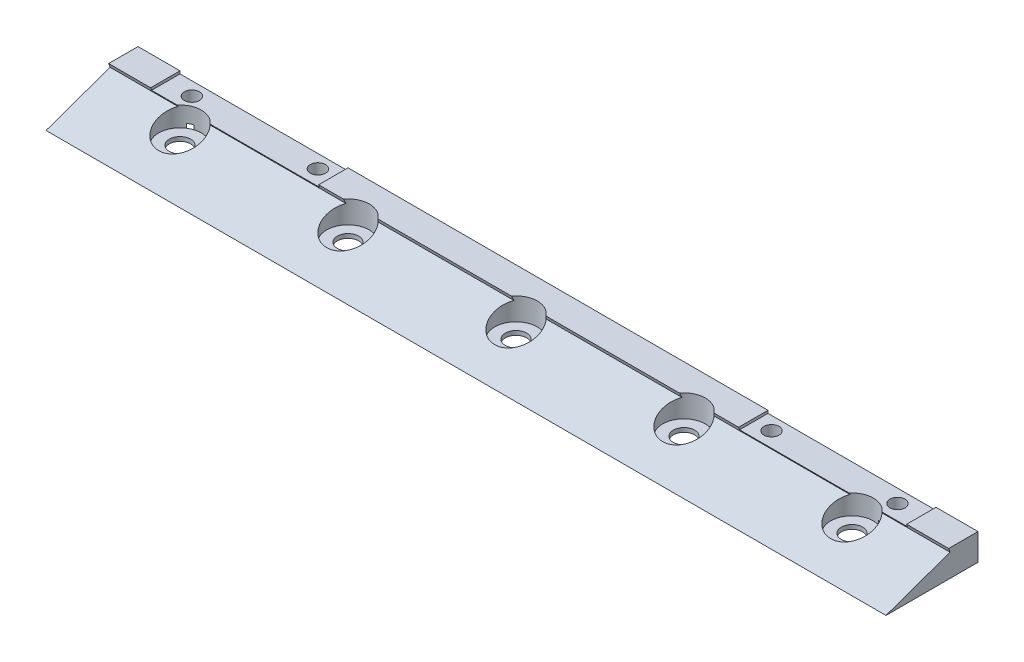
SolidWorks part; units mm, degrees
material "1023 Carbon Steel Sheet (SS)"
ref_plane "Front Plane" through (0, 0, 0) normal (0, 0, 1) x (1, 0, 0)
ref_plane "Top Plane" through (0, 0, 0) normal (0, 1, 0) x (1, 0, 0)
ref_plane "Right Plane" through (0, 0, 0) normal (1, 0, 0) x (0, 0, -1)
sketch "Sketch1" plane through (0, 0, 0) normal (0, 1, 0) x (1, 0, 0)
  line L1 (-100, -15) -> (100, -15)
  line L2 (-100, -15) -> (-100, 15)
  line L3 (-100, 15) -> (100, 15)
  line L4 (100, -15) -> (100, 15)
  line L5 (-100, -15) -> (100, 15) construction
  line L6 (-100, 15) -> (100, -15) construction
  point P0 (0, 0)
  dimension "D1" = 200
  dimension "D2" = 30
extrude "Base" add sketch "Sketch1" along normal blind 6.35
ref_plane "Midplane" through (0, 0, 0) normal (1, 0, 0) x (0, 0, -1)
sketch "Sketch2" plane through (100, 0, 0) normal (1, 0, 0) x (0, 0, -1)
  line L0 (-6.9075, 0) -> (11, 6.35)
  line L1 (-15, 0) -> (15, 0) construction
  line L2 (-15, 6.35) -> (15, 6.35) construction
  line L3 (11, 6.35) -> (11, 0)
  line L4 (11, 0) -> (-6.9075, 0)
  line L5 (15, 6.35) -> (15, 0) construction
  line L7 (11, 6.35) -> (-15, 6.35)
  line L8 (-15, 6.35) -> (-15, 0)
  line L9 (-15, 0) -> (-6.9075, 0)
  line L10 (8.3421, 5.4075) -> (8.0079, 6.35)
  line M3 (-15, 0) -> (15, 0)
  line M5 (15, 6.35) -> (-15, 6.35)
  line M6 (-15, 6.35) -> (-15, 0)
  dimension "D1" = 19
  dimension "D2" = 4
  dimension "D3" = 1
extrude "WedgeCut" cut sketch "Sketch2" against normal up to next contours L0 M3 M5 M6
sketch "Sketch3" plane through (0, 6.35, 0) normal (0, 1, 0) x (1, 0, 0)
  line L0 (-100, 15) -> (-100, 8.0079) construction
  line L1 (-90, 7) -> (-50, 7)
  line L2 (-90, 7) -> (-90, 15)
  line L3 (-90, 15) -> (-50, 15)
  line L4 (-50, 7) -> (-50, 15)
  line L5 (-90, 7) -> (-50, 15) construction
  line L6 (-90, 15) -> (-50, 7) construction
  line L7 (50, 15) -> (90, 15)
  line L8 (50, 15) -> (50, 7)
  line L9 (50, 7) -> (90, 7)
  line L10 (90, 15) -> (90, 7)
  line L11 (50, 15) -> (90, 7) construction
  line L12 (50, 7) -> (90, 15) construction
  line L13 (100, 15) -> (-100, 15) construction
  line L14 (100, 8.0079) -> (100, 15) construction
  point P0 (-70, 11)
  point P5 (70, 11)
  dimension "D1" = 8
  dimension "D2" = 40
  dimension "D3" = 10
  dimension "D4" = 40
  dimension "D5" = 10
  dimension "D6" = 8
extrude "Hinge Cutout" cut sketch "Sketch3" against normal blind 0.635
sketch "Sketch4" plane through (0, 5.715, 0) normal (0, 1, 0) x (1, 0, 0)
  line L0 (90, 15) -> (50, 15) construction
  line L1 (90, 8.0079) -> (90, 15) construction
  circle A0 centre (54, 11.825) radius 1.8034
  circle A1 centre (84, 11.825) radius 1.8034
  dimension "D5" = 3.6068
  dimension "D6" = 3.6068
  dimension "D1" = 6
  dimension "D2" = 30
  dimension "D3" = 3.175
  dimension "D4" = 3.175
extrude "Hinge Hole Cut" cut sketch "Sketch4" against normal up to next
sketch "Sketch5" plane through (0, 0, 0) normal (0, -1, 0) x (1, 0, 0)
  line L1 (51.475, -14.35) -> (56.525, -14.35)
  line L2 (51.475, -14.35) -> (51.475, -9.3)
  line L3 (51.475, -9.3) -> (56.525, -9.3)
  line L4 (56.525, -14.35) -> (56.525, -9.3)
  line L5 (51.475, -14.35) -> (56.525, -9.3) construction
  line L6 (51.475, -9.3) -> (56.525, -14.35) construction
  line L7 (81.475, -14.35) -> (86.525, -14.35)
  line L8 (81.475, -14.35) -> (81.475, -9.3)
  line L9 (81.475, -9.3) -> (86.525, -9.3)
  line L10 (86.525, -14.35) -> (86.525, -9.3)
  line L11 (81.475, -14.35) -> (86.525, -9.3) construction
  line L12 (81.475, -9.3) -> (86.525, -14.35) construction
  point P0 (54, -11.825)
  point P6 (84, -11.825)
  dimension "D1" = 5.05
  dimension "D2" = 5.05
  dimension "D3" = 5.05
  dimension "D4" = 5.05
extrude "Hinge Nut Cut" cut sketch "Sketch5" against normal blind 2
mirror "Hinge Hole Mirror" about plane through (0, 0, 0) normal (1, 0, 0) of "Hinge Nut Cut", "Hinge Hole Cut"
sketch "Sketch6" plane through (0, 0, 0) normal (0, -1, 0) x (-1, 0, 0)
  circle A0 centre (-80, 5) radius 5.08
  circle A1 centre (-40, 5) radius 5.08
  circle A2 centre (0, 5) radius 5.08
  circle A3 centre (40, 5) radius 5.08
  circle A4 centre (80, 5) radius 5.08
  dimension "D1" = 40
  dimension "D2" = 40
  dimension "D3" = 40
  dimension "D4" = 40
  dimension "D5" = 10.16
  dimension "D6" = 5
extrude "Cut-Extrude1" cut sketch "Sketch6" against normal through all
sketch "Sketch7" plane through (0, 0, 0) normal (0, -1, 0) x (1, 0, 0)
  circle A1 centre (-80, -5) radius 5.08
  arc A2 (-80.7375, -7.4306) -> (-81.3524, -7.15) centre (-80, -5) ccw
  circle A3 centre (-80, -5) radius 2.54
  circle A4 centre (-40, -5) radius 5.08
  circle A5 centre (0, -5) radius 5.08
  circle A6 centre (40, -5) radius 5.08
  circle A7 centre (80, -5) radius 5.08
  circle A8 centre (80, -5) radius 2.54
  circle A9 centre (-40, -5) radius 2.54
  circle A10 centre (0, -5) radius 2.54
  circle A11 centre (40, -5) radius 2.54
  dimension "D1" = 2.54
  dimension "D2" = 2.54
extrude "Boss-Extrude1" add sketch "Sketch7" against normal blind 1
